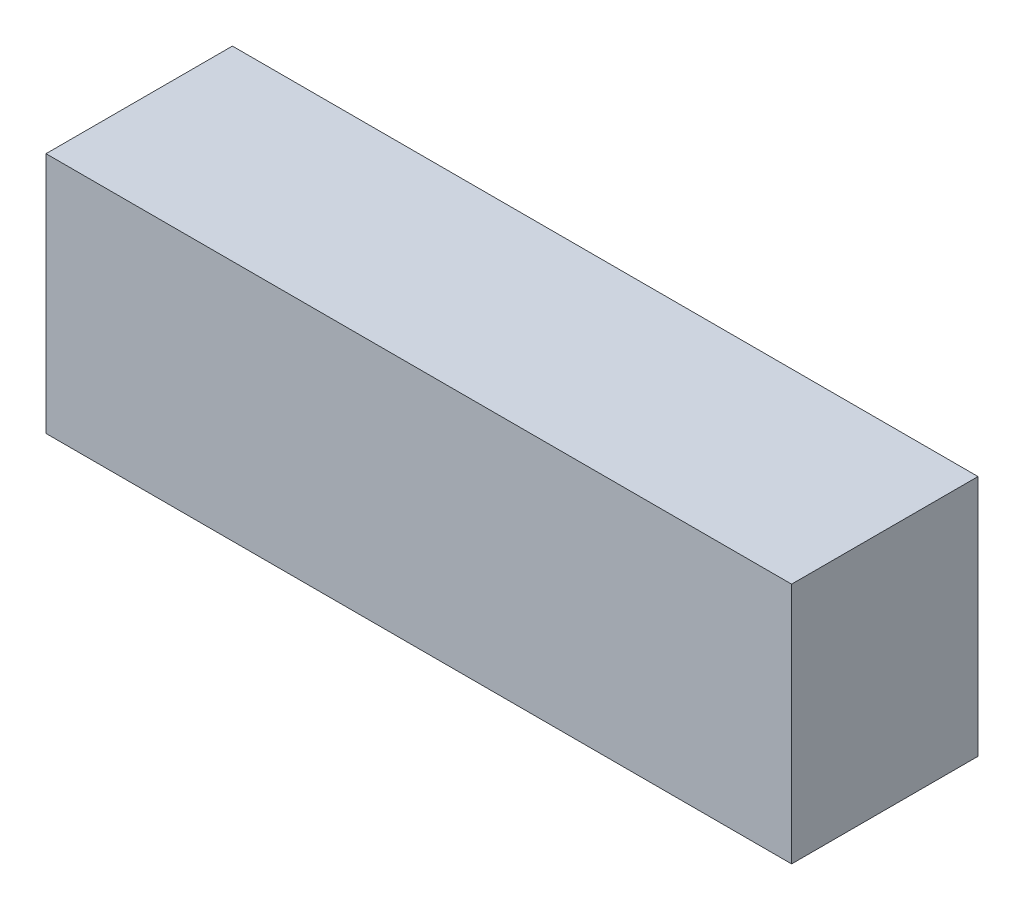
SolidWorks part; units mm, degrees
ref_plane "Front Plane" through (0, 0, 0) normal (0, 0, 1) x (1, 0, 0)
ref_plane "Top Plane" through (0, 0, 0) normal (0, 1, 0) x (1, 0, 0)
ref_plane "Right Plane" through (0, 0, 0) normal (1, 0, 0) x (0, 0, -1)
sketch "Sketch1" plane through (0, 0, 0) normal (0, 0, 1) x (1, 0, 0)
  line L1 (0, 0) -> (40, 0)
  line L2 (0, 0) -> (0, 13)
  line L3 (0, 13) -> (40, 13)
  line L4 (40, 0) -> (40, 13)
extrude "Boss-Extrude1" add sketch "Sketch1" along normal blind 10
